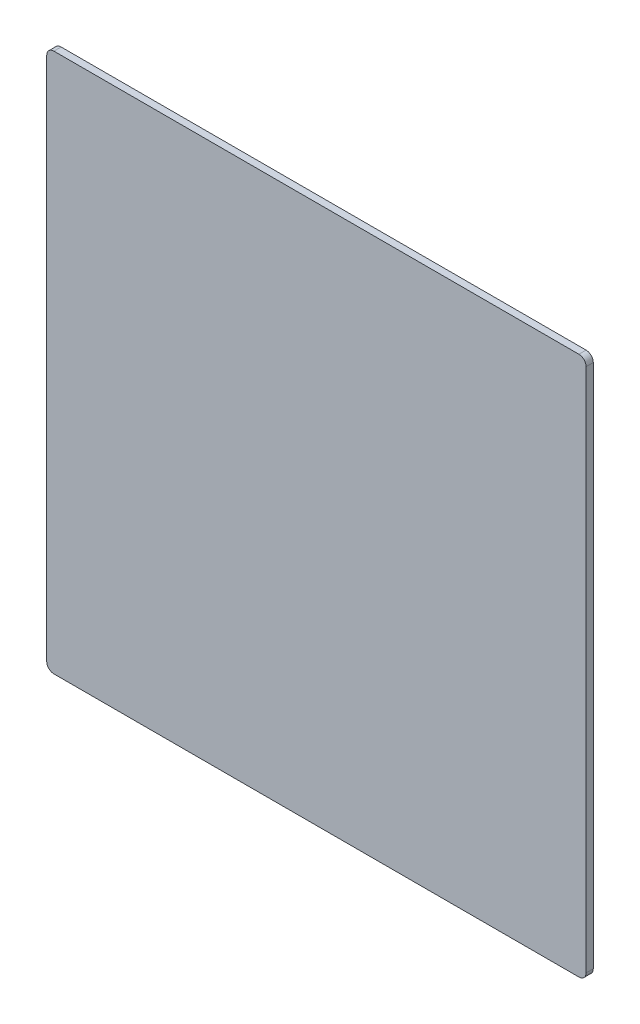
SolidWorks part; units mm, degrees
ref_plane "Front Plane" through (0, 0, 0) normal (0, 0, 1) x (1, 0, 0)
ref_plane "Top Plane" through (0, 0, 0) normal (0, 1, 0) x (1, 0, 0)
ref_plane "Right Plane" through (0, 0, 0) normal (1, 0, 0) x (0, 0, -1)
sketch "Sketch1" plane through (0, 0, 0) normal (0, 0, 1) x (1, 0, 0)
  line L1 (-73, 75) -> (73, 75)
  line L2 (-75, 73) -> (-75, -73)
  line L3 (-73, -75) -> (73, -75)
  line L4 (75, 73) -> (75, -73)
  line L5 (-75, 75) -> (75, -75) construction
  line L6 (-75, -75) -> (75, 75) construction
  arc A0 (-75, -73) -> (-73, -75) centre (-73, -73) ccw
  arc A1 (73, -75) -> (75, -73) centre (73, -73) ccw
  arc A2 (73, 75) -> (75, 73) centre (73, 73) cw
  arc A3 (-73, 75) -> (-75, 73) centre (-73, 73) ccw
  point P0 (0, 0)
  dimension "D1" = 2
extrude "Boss-Extrude1" add sketch "Sketch1" along normal blind 2
